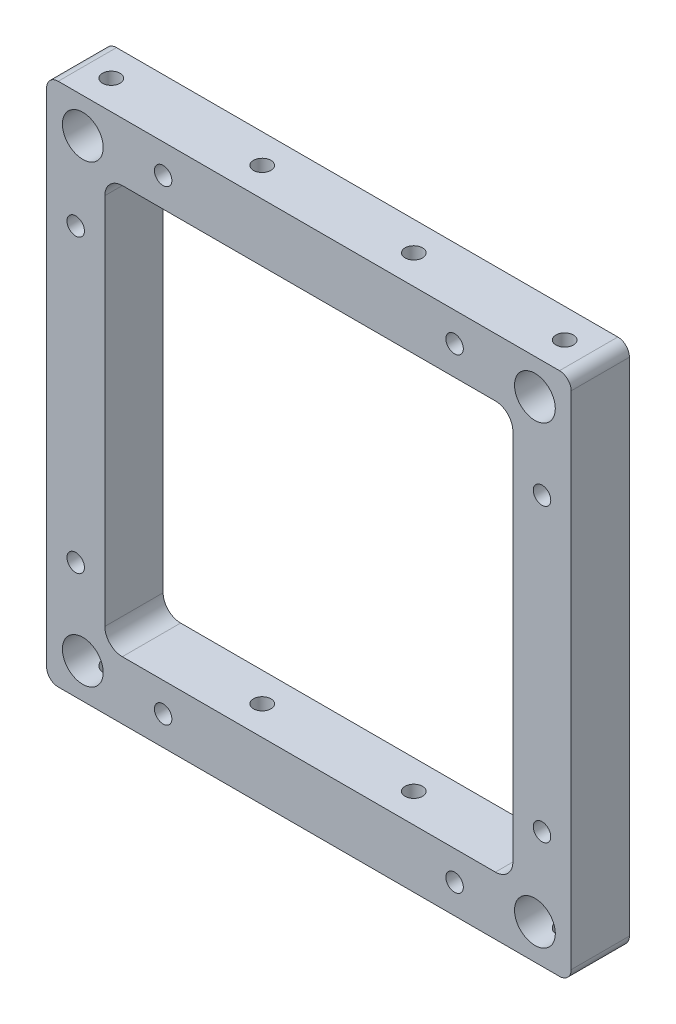
SolidWorks part; units mm, degrees
ref_plane "Front Plane" through (0, 0, 0) normal (0, 0, 1) x (1, 0, 0)
ref_plane "Top Plane" through (0, 0, 0) normal (0, 1, 0) x (1, 0, 0)
ref_plane "Right Plane" through (0, 0, 0) normal (1, 0, 0) x (0, 0, -1)
sketch "Sketch1" plane through (0, 0, 0) normal (0, 0, 1) x (1, 0, 0)
  line L0 (-45, 0) -> (45, 0) construction
  line L1 (45, -6) -> (-45, -6)
  line L2 (45, -6) -> (45, 6)
  line L3 (35, 4) -> (-35, 4)
  line L4 (-45, -6) -> (-45, 6)
  line L5 (45, -6) -> (0, 0) construction
  line L6 (45, 6) -> (-45, -6) construction
  line L7 (0, 4) -> (0, -5.9098) construction
  line L8 (-50.4363, 39) -> (55.0192, 39) construction
  line L9 (45, 84) -> (45, 72)
  line L10 (45, 84) -> (-45, 84)
  line L11 (-45, 84) -> (-45, 72)
  line L12 (35, 74) -> (-35, 74)
  line L13 (45, 72) -> (45, 6)
  line L14 (-45, 72) -> (-45, 6)
  line L15 (-35, 74) -> (-35, 4)
  line L16 (35, 74) -> (35, 4)
  line L17 (0, 84) -> (0, -5.9098) construction
  circle A0 centre (-38.7814, 0) radius 3.5
  circle A1 centre (38.7814, 0) radius 3.5
  circle A2 centre (-38.7814, 78) radius 3.5
  circle A3 centre (38.7814, 78) radius 3.5
  point P0 (0, 0)
  dimension "D4" = 7
  dimension "D8" = 6
  dimension "D1" = 10
  dimension "D2" = 90
  dimension "D3" = 110
  dimension "D5" = 90
  dimension "D6" = 10
  dimension "D7" = 10
  dimension "D9" = 45
  dimension "D10" = 10
extrude "Boss-Extrude1" add sketch "Sketch1" along normal blind 10
fillet "Fillet3" radius 2 4 edges at (-45, 84, 5) (45, 84, 5) (45, -6, 5) (-45, -6, 5)
sketch "Sketch3" plane through (0, -6, 0) normal (0, -1, 0) x (1, 0, 0)
  line L0 (-43, 5) -> (43, 5) construction
  line L1 (-43, 10) -> (-43, 0) construction
  line L2 (43, 0) -> (43, 10) construction
  line L3 (0, 0) -> (0, 10) construction
  line L4 (-43, 10) -> (43, 10) construction
  circle A0 centre (-13, 5) radius 1.5
  circle A1 centre (13, 5) radius 1.5
  dimension "D1" = 26
  dimension "D2" = 3
extrude "Cut-Extrude2" cut sketch "Sketch3" against normal blind 90
sketch "Sketch5" plane through (0, -6, 0) normal (0, -1, 0) x (1, 0, 0)
  line L0 (-43, 5) -> (43, 5) construction
  line L1 (-43, 10) -> (-43, 0) construction
  line L2 (43, 0) -> (43, 10) construction
  line L3 (0, 0) -> (0, 10) construction
  line L4 (-43, 0) -> (43, 0) construction
  line L5 (-43, 10) -> (43, 10) construction
  circle A0 centre (-38.89, 5) radius 1.5
  circle A1 centre (38.89, 5) radius 1.5
  dimension "D1" = 77.78
  dimension "D2" = 3
extrude "Cut-Extrude4" cut sketch "Sketch5" against normal up to next
sketch "Sketch6" plane through (0, 84, 0) normal (0, 1, 0) x (1, 0, 0)
  line L0 (-43, -5) -> (43, -5) construction
  line L1 (-43, 0) -> (-43, -10) construction
  line L2 (43, -10) -> (43, 0) construction
  line L3 (0, 0) -> (0, -10) construction
  line L5 (43, -10) -> (-43, -10) construction
  circle A0 centre (-38.89, -5) radius 1.5
  circle A1 centre (38.89, -5) radius 1.5
  dimension "D1" = 77.78
  dimension "D2" = 3
extrude "Cut-Extrude5" cut sketch "Sketch6" against normal up to next
fillet "Fillet5" radius 3 4 edges at (35, 74, 5) (35, 4, 5) (-35, 4, 5) (-35, 74, 5)
sketch "Sketch7" plane through (0, 0, 10) normal (0, 0, 1) x (1, 0, 0)
  line L0 (0, 84) -> (0, -6) construction
  line L1 (43, 84) -> (-43, 84) construction
  line L2 (-43, -6) -> (43, -6) construction
  line L3 (-45, 39) -> (45, 39) construction
  line L4 (-45, 82) -> (-45, -4) construction
  line L5 (45, -4) -> (45, 82) construction
  line L6 (-30.3822, 79) -> (27.4035, 79) construction
  line L7 (38.7814, 78) -> (-38.7814, 0) construction
  line L8 (40, 68.429) -> (40, 14.0985) construction
  circle A0 centre (-25, 79) radius 1.5
  circle A1 centre (25, 79) radius 1.5
  circle A2 centre (25, -1) radius 1.5
  circle A3 centre (-25, -1) radius 1.5
  circle A6 centre (40, 64) radius 1.5
  circle A7 centre (40, 14) radius 1.5
  circle A8 centre (-40, 14) radius 1.5
  circle A9 centre (-40, 64) radius 1.5
  dimension "D3" = 3
  dimension "D4" = 5
  dimension "D5" = 50
  dimension "D6" = 3
  dimension "D1" = 5
  dimension "D2" = 50
extrude "Cut-Extrude6" cut sketch "Sketch7" against normal up to next
